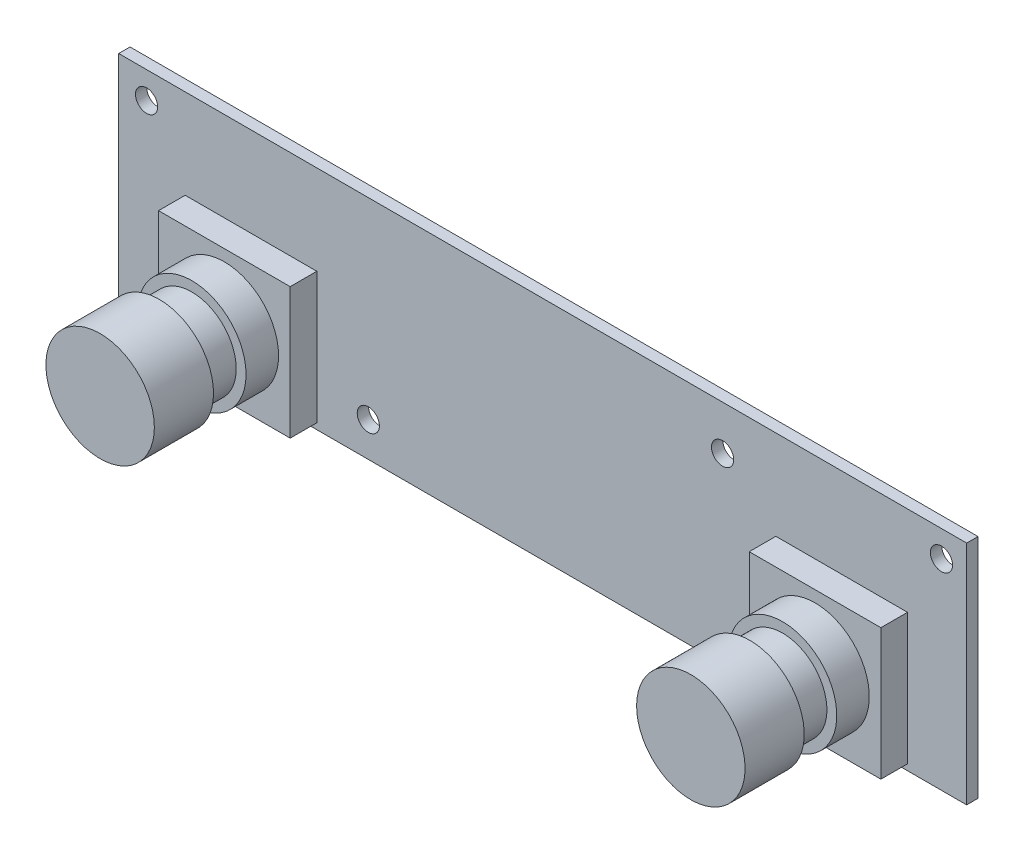
SolidWorks part; units mm, degrees
ref_plane "Front Plane" through (0, 0, 0) normal (0, 0, 1) x (1, 0, 0)
ref_plane "Top Plane" through (0, 0, 0) normal (0, 1, 0) x (1, 0, 0)
ref_plane "Right Plane" through (0, 0, 0) normal (1, 0, 0) x (0, 0, -1)
sketch "Sketch1" plane through (0, 0, 0) normal (0, 0, 1) x (1, 0, 0)
  line L1 (-43, -11.5) -> (43, -11.5)
  line L2 (-43, -11.5) -> (-43, 11.5)
  line L3 (-43, 11.5) -> (43, 11.5)
  line L4 (43, -11.5) -> (43, 11.5)
  point P6 (0, 0)
  dimension "D1" = 86
  dimension "D2" = 23
extrude "Boss-Extrude1" add sketch "Sketch1" against normal blind 1.15 contours L2 L1 L4 L3
sketch "Sketch2" plane through (0, 0, 0) normal (0, 0, 1) x (1, 0, 0)
  line L0 (-36.26, 2.4178) -> (-22.91, 2.4178)
  line L1 (23.65, 2.4178) -> (37, 2.4178)
  line L2 (23.65, 2.4178) -> (23.65, -10.8922)
  line L3 (23.65, -10.8922) -> (37, -10.8922)
  line L4 (37, 2.4178) -> (37, -10.8922)
  line L5 (-36.26, 2.4178) -> (-36.26, -10.8922)
  line L6 (-36.26, -10.8922) -> (-22.91, -10.8922)
  line L7 (-22.91, 2.4178) -> (-22.91, -10.8922)
  dimension "D1" = 13.35
  dimension "D2" = 13.31
  dimension "D3" = 6
  dimension "D4" = 46.56
extrude "Boss-Extrude2" add sketch "Sketch2" along normal blind 2.7
ref_plane "Plane1" through (0, 0, 2.7) normal (0, 0, 1) x (1, 0, 0)
sketch "Sketch3" plane through (0, 0, 2.7) normal (0, 0, 1) x (1, 0, 0)
  line L0 (-36.26, 2.4178) -> (-36.26, -10.8922) construction
  line L1 (37, -10.8922) -> (37, 2.4178) construction
  line L2 (-36.26, -4.2372) -> (37, -4.2372) construction
  line L3 (0.37, -4.2372) -> (0.37, 19.7115) construction
  line L4 (-29.585, 2.4178) -> (-29.585, -10.8922) construction
  line L5 (-22.91, 2.4178) -> (-36.26, 2.4178) construction
  line L6 (-36.26, -10.8922) -> (-22.91, -10.8922) construction
  line L7 (30.325, 2.4178) -> (30.325, -10.8922) construction
  line L8 (37, 2.4178) -> (23.65, 2.4178) construction
  line L9 (23.65, -10.8922) -> (37, -10.8922) construction
  circle A0 centre (-29.585, -4.2372) radius 5.5
  point P0 (-36.26, -4.2372)
  point P1 (37, -4.2372)
  point P26 (-29.585, -4.2372)
  point P27 (30.325, -4.2372)
ref_plane "Plane2" through (0.37, 0, 0) normal (1, 0, 0) x (0, 0, -1)
extrude "Boss-Extrude3" add sketch "Sketch3" along normal blind 3.3
sketch "Sketch5" plane through (0, 0, 6) normal (0, 0, 1) x (1, 0, 0)
  circle A0 centre (-29.585, -4.2372) radius 4.5
extrude "Boss-Extrude4" add sketch "Sketch5" along normal blind 3.3
ref_plane "Plane3" through (0, 0, 9.3) normal (0, 0, 1) x (1, 0, 0)
sketch "Sketch6" plane through (0, 0, 9.3) normal (0, 0, 1) x (1, 0, 0)
  line L0 (-29.585, 0.2628) -> (-29.585, -8.7372) construction
  line L1 (-34.085, -4.2372) -> (-25.085, -4.2372) construction
  circle A0 centre (-29.585, -4.2372) radius 4.5 construction
  circle A1 centre (-29.585, -4.2372) radius 4.5 construction
  circle A2 centre (-29.585, -4.2372) radius 5.5
extrude "Boss-Extrude5" add sketch "Sketch6" along normal blind 6
mirror "Mirror1" about plane through (0.37, 0, 0) normal (1, 0, 0) of "Boss-Extrude3", "Boss-Extrude4", "Boss-Extrude5"
sketch "Sketch7" plane through (0, 0, -1.15) normal (0, 0, -1) x (-1, 0, 0)
  line L0 (43, -11.5) -> (-43, -11.5) construction
  line L2 (-43, 0) -> (43, 0) construction
  line L3 (-43, -11.5) -> (-43, 11.5) construction
  line L4 (43, -11.5) -> (43, 11.5) construction
  line L5 (43, 11.5) -> (-43, 11.5) construction
  circle A17 centre (40.175, 8.775) radius 1.125
  circle A18 centre (17.685, -7.995) radius 1.125
  circle A19 centre (-18.245, 6.995) radius 1.125
  circle A20 centre (-40.445, 8.8358) radius 1.125
  point P0 (-18.245, 8.12)
  point P11 (-19.37, 6.995)
  point P14 (17.685, -9.12)
  point P15 (-41.57, 8.8358)
  point P16 (18.81, -7.995)
  point P19 (41.3, 8.775)
  point P20 (40.175, 9.9)
  dimension "D1" = 3.38
  dimension "D2" = 1.43
  dimension "D7" = 1.7
  dimension "D8" = 2.25
  dimension "D3" = 23.63
  dimension "D4" = 2.38
  dimension "D5" = 24.19
  dimension "D6" = 1.6
extrude "Cut-Extrude1" cut sketch "Sketch7" against normal blind 3
